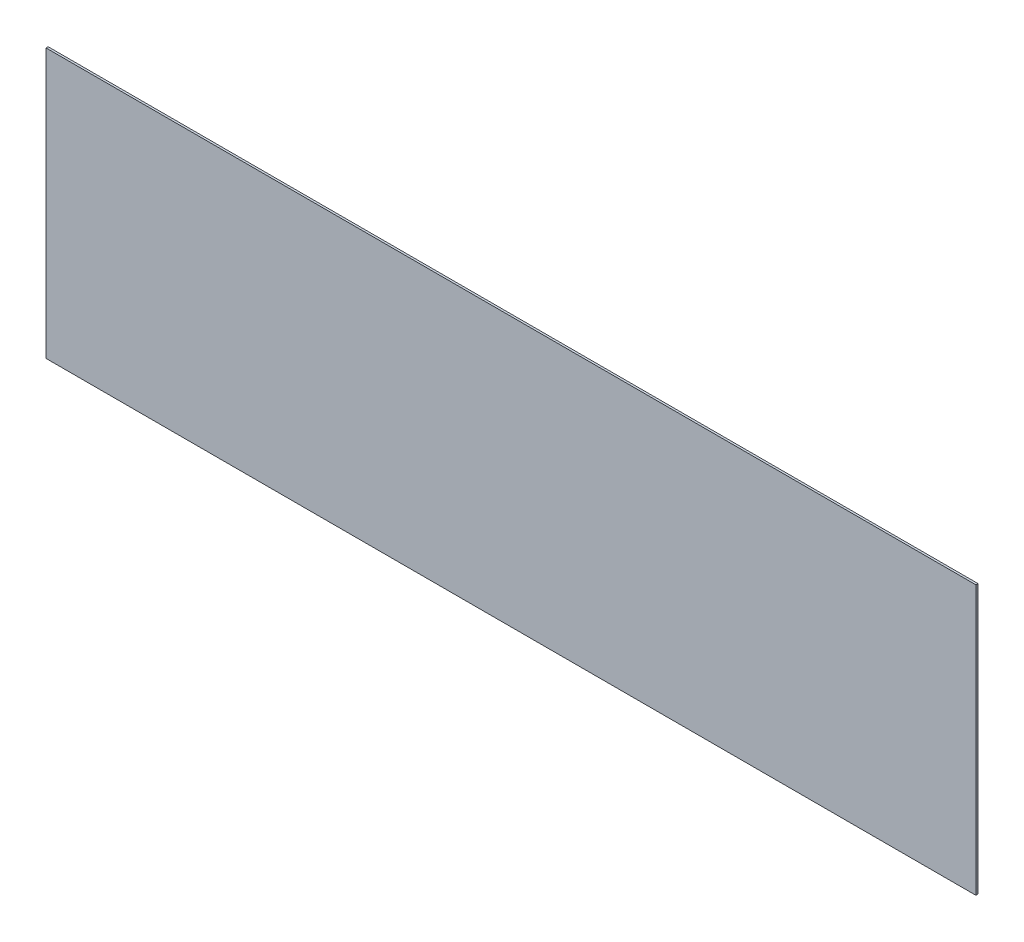
SolidWorks part; units mm, degrees
ref_plane "Front Plane" through (0, 0, 0) normal (0, 0, 1) x (1, 0, 0)
ref_plane "Top Plane" through (0, 0, 0) normal (0, 1, 0) x (1, 0, 0)
ref_plane "Right Plane" through (0, 0, 0) normal (1, 0, 0) x (0, 0, -1)
other "Configuration Table"
sketch "Sketch1" plane through (0, 0, 0) normal (0, 0, 1) x (1, 0, 0)
  line L1 (21.5, 10) -> (678.5, 10)
  line L2 (21.5, 10) -> (21.5, 200)
  line L3 (21.5, 200) -> (678.5, 200)
  line L4 (678.5, 10) -> (678.5, 200)
extrude "TOPPING_plint_arka_1" add sketch "Sketch1" against normal blind 1.5 from offset 798.5 separate body
